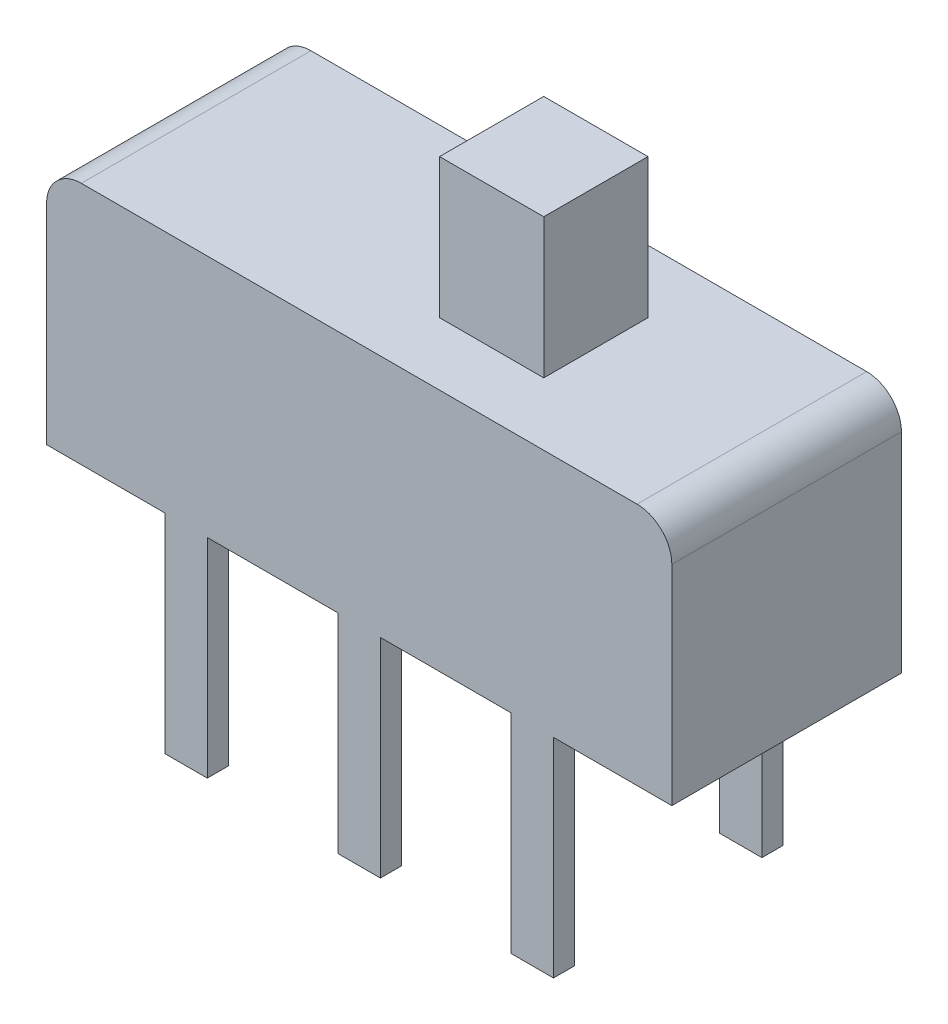
SolidWorks part; units mm, degrees
ref_plane "Front Plane" through (0, 0, 0) normal (0, 0, 1) x (1, 0, 0)
ref_plane "Top Plane" through (0, 0, 0) normal (0, 1, 0) x (1, 0, 0)
ref_plane "Right Plane" through (0, 0, 0) normal (1, 0, 0) x (0, 0, -1)
sketch "Sketch1" plane through (0, 0, 0) normal (0, 1, 0) x (1, 0, 0)
  line L0 (-4.4958, -1.651) -> (4.4958, -1.651)
  line L1 (-4.4958, -1.651) -> (-4.4958, 1.651)
  line L2 (4.4958, -1.651) -> (4.4958, 1.651)
  line L3 (-4.4958, 1.651) -> (4.4958, 1.651)
  line L4 (-4.4958, -1.651) -> (4.4958, 1.651) construction
  line L5 (4.4958, -1.651) -> (-4.4958, 1.651) construction
  point P1 (0, 0)
  dimension "D1" = 8.9916
  dimension "D2" = 3.302
extrude "Boss-Extrude1" add sketch "Sketch1" along normal blind 3.5052
sketch "Sketch2" plane through (0, 3.5052, 0) normal (0, 1, 0) x (1, 0, 0)
  line L0 (0.254, -0.7493) -> (1.7526, -0.7493)
  line L1 (0.254, -0.7493) -> (0.254, 0.7493)
  line L2 (1.7526, -0.7493) -> (1.7526, 0.7493)
  line L3 (0.254, 0.7493) -> (1.7526, 0.7493)
  line L4 (0.254, -0.7493) -> (1.7526, 0.7493) construction
  line L5 (1.7526, -0.7493) -> (0.254, 0.7493) construction
  line L6 (4.4958, 1.651) -> (-4.4958, 1.651) construction
  point P1 (1.0033, 0)
  dimension "D1" = 1.4986
  dimension "D2" = 1.4986
  dimension "D3" = 0
  dimension "D4" = 1.0033
extrude "Boss-Extrude2" add sketch "Sketch2" along normal blind 2.0066
sketch "Sketch3" plane through (0, 0, 0) normal (0, -1, 0) x (1, 0, 0)
  line L0 (2.1844, 1.3462) -> (2.794, 1.3462)
  line L1 (2.1844, 1.3462) -> (2.1844, 1.651)
  line L2 (2.794, 1.3462) -> (2.794, 1.651)
  line L3 (2.1844, 1.651) -> (2.794, 1.651)
  line L4 (2.1844, 1.3462) -> (2.794, 1.651) construction
  line L5 (2.794, 1.3462) -> (2.1844, 1.651) construction
  line L6 (-4.4958, 1.651) -> (4.4958, 1.651) construction
  point P1 (2.4892, 1.4986)
  dimension "D1" = 0.3048
  dimension "D2" = 0.6096
  dimension "D3" = 2.4892
extrude "Boss-Extrude3" add sketch "Sketch3" along normal blind 2.9972
pattern_linear "LPattern1" count 3 spacing 2.4892 along (-1, 0, 0) of "Boss-Extrude3"
mirror "Mirror1" about plane through (0, 0, 0) normal (0, 0, 1) of "LPattern1", "Boss-Extrude3"
fillet "Fillet1" radius 0.5 2 edges at (4.4958, 3.5052, 0) (-4.4958, 3.5052, 0)
